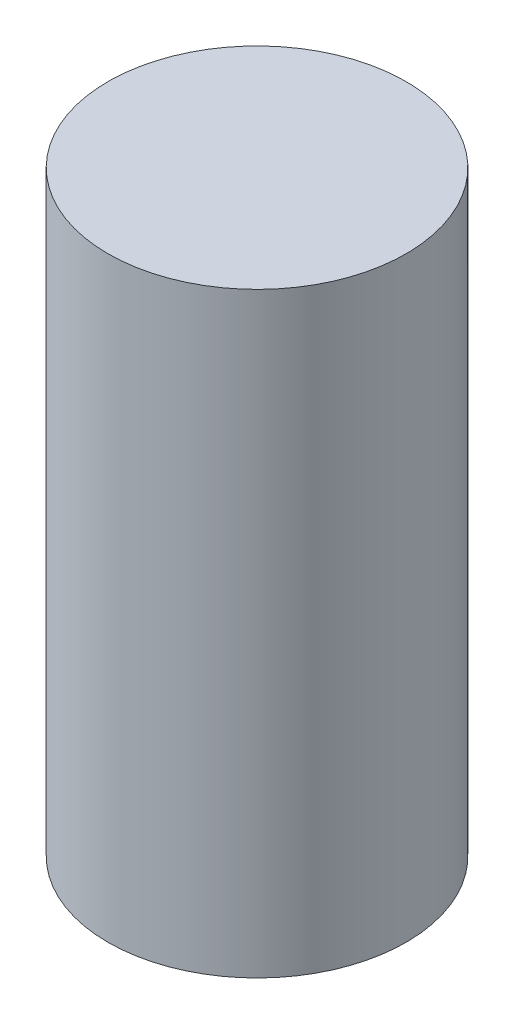
SolidWorks part; units mm, degrees
ref_plane "Plano frontal" through (0, 0, 0) normal (0, 0, 1) x (1, 0, 0)
ref_plane "Plano superior" through (0, 0, 0) normal (0, 1, 0) x (1, 0, 0)
ref_plane "Plano direito" through (0, 0, 0) normal (1, 0, 0) x (0, 0, -1)
sketch "Esboço1" plane through (0, 0, 0) normal (0, 1, 0) x (1, 0, 0)
  circle A0 centre (0, 0) radius 15
  dimension "D1" = 30
extrude "Ressalto-extrusão1" add sketch "Esboço1" along normal blind 60
sketch "Esboço2" plane through (0, 0, 0) normal (0, -1, 0) x (1, 0, 0)
  line L0 (0, 15) -> (0, 0)
  circle A0 centre (0, 0) radius 15 construction
